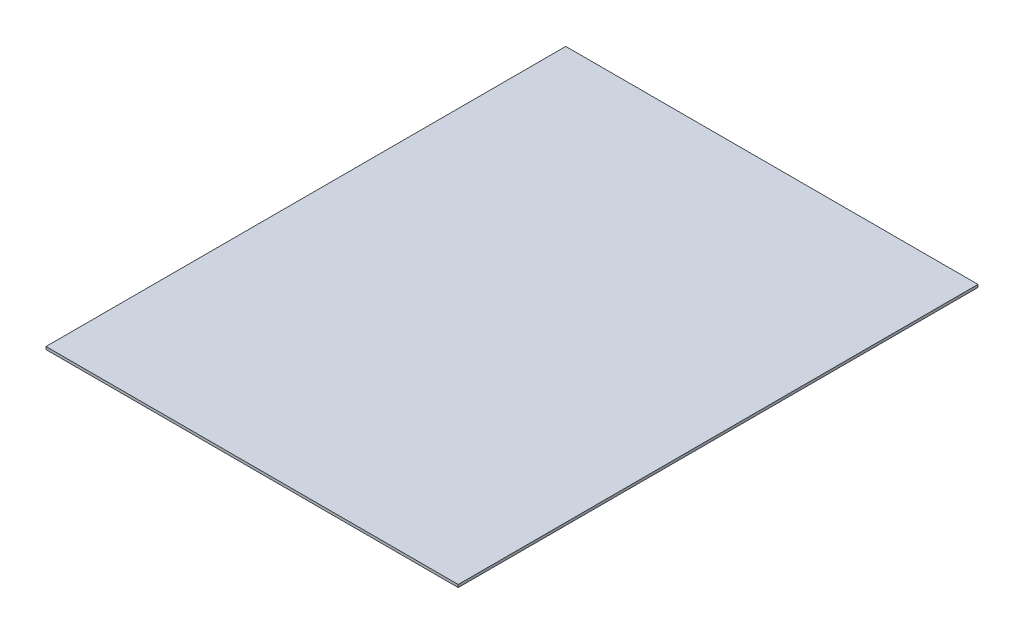
SolidWorks part; units mm, degrees
ref_plane "Front Plane" through (0, 0, 0) normal (0, 0, 1) x (1, 0, 0)
ref_plane "Top Plane" through (0, 0, 0) normal (0, 1, 0) x (1, 0, 0)
ref_plane "Right Plane" through (0, 0, 0) normal (1, 0, 0) x (0, 0, -1)
sketch "Sketch1" plane through (0, 0, 0) normal (0, 1, 0) x (1, 0, 0)
  line L1 (-230, 290) -> (230, 290)
  line L2 (-230, 290) -> (-230, -290)
  line L3 (-230, -290) -> (230, -290)
  line L4 (230, 290) -> (230, -290)
  line L5 (-230, 290) -> (230, -290) construction
  line L6 (-230, -290) -> (230, 290) construction
  point P0 (0, 0)
  dimension "D1" = 460
  dimension "D2" = 580
extrude "Boss-Extrude1" add sketch "Sketch1" along normal blind 3
